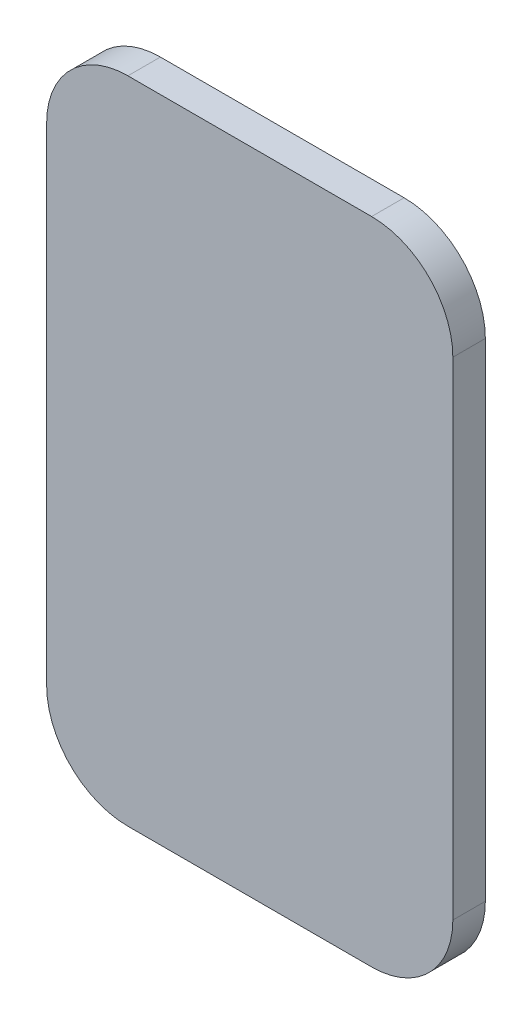
SolidWorks part; units mm, degrees
ref_plane "Alzado" through (0, 0, 0) normal (0, 0, 1) x (1, 0, 0)
ref_plane "Planta" through (0, 0, 0) normal (0, 1, 0) x (1, 0, 0)
ref_plane "Vista lateral" through (0, 0, 0) normal (1, 0, 0) x (0, 0, -1)
sketch "Croquis1" plane through (0, 0, 0) normal (0, 0, 1) x (1, 0, 0)
  line L1 (-21.0832, 42.8317) -> (-6.0832, 42.8317)
  line L2 (-26.0832, 37.8317) -> (-26.0832, 7.8317)
  line L3 (-21.0832, 2.8317) -> (-6.0832, 2.8317)
  line L4 (-1.0832, 37.8317) -> (-1.0832, 7.8317)
  arc A0 (-21.0832, 2.8317) -> (-26.0832, 7.8317) centre (-21.0832, 7.8317) cw
  arc A1 (-1.0832, 7.8317) -> (-6.0832, 2.8317) centre (-6.0832, 7.8317) cw
  arc A2 (-1.0832, 37.8317) -> (-6.0832, 42.8317) centre (-6.0832, 37.8317) ccw
  arc A3 (-21.0832, 42.8317) -> (-26.0832, 37.8317) centre (-21.0832, 37.8317) ccw
  point P6 (-26.0832, 2.8317)
  point P9 (-1.0832, 2.8317)
  point P14 (-26.0832, 42.8317)
  dimension "D3" = 5
  dimension "D1" = 40
  dimension "D2" = 25
extrude "Saliente-Extruir1" add sketch "Croquis1" along normal blind 2
